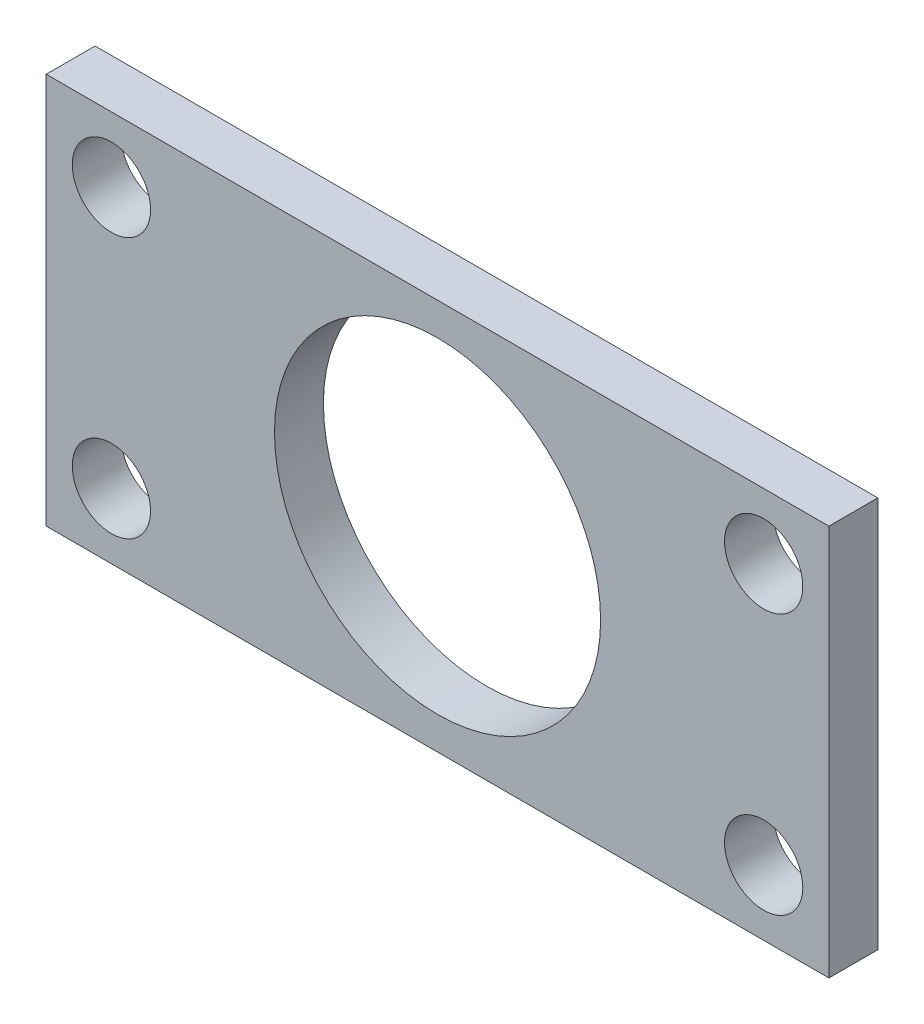
SolidWorks part; units mm, degrees
ref_plane "Front Plane" through (0, 0, 0) normal (0, 0, 1) x (1, 0, 0)
ref_plane "Top Plane" through (0, 0, 0) normal (0, 1, 0) x (1, 0, 0)
ref_plane "Right Plane" through (0, 0, 0) normal (1, 0, 0) x (0, 0, -1)
sketch "Sketch1" plane through (0, 0, 0) normal (0, 0, 1) x (1, 0, 0)
  line L0 (12, 20.3627) -> (12, -5.043) construction
  line L1 (0, 0) -> (24, 0)
  line L2 (0, 0) -> (0, 12)
  line L3 (0, 12) -> (24, 12)
  line L4 (24, 0) -> (24, 12)
  line L5 (-3.9986, 6) -> (30.4891, 6) construction
  circle A0 centre (2, 10) radius 1.2
  circle A1 centre (22, 10) radius 1.2
  circle A2 centre (22, 2) radius 1.2
  circle A3 centre (2, 2) radius 1.2
  circle A4 centre (12, 6) radius 5
  dimension "D3" = 2.4
  dimension "D8" = 10
  dimension "D1" = 24
  dimension "D2" = 12
  dimension "D4" = 2
  dimension "D5" = 2
  dimension "D6" = 12
  dimension "D7" = 6
extrude "Boss-Extrude1" add sketch "Sketch1" along normal blind 1.5
